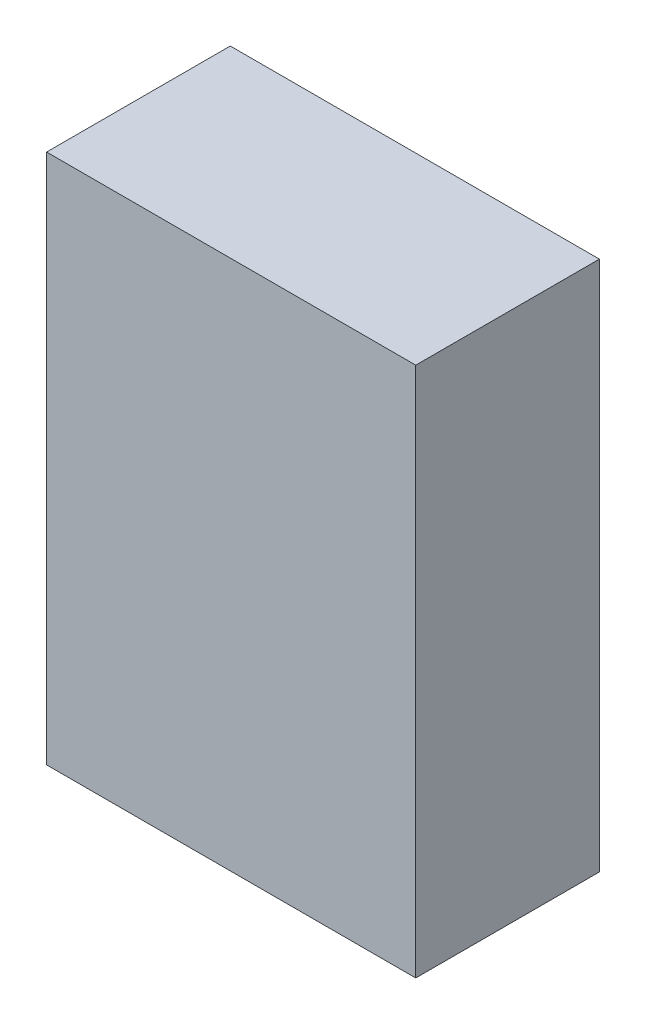
SolidWorks part; units mm, degrees
ref_plane "Front Plane" through (0, 0, 0) normal (0, 0, 1) x (1, 0, 0)
ref_plane "Top Plane" through (0, 0, 0) normal (0, 1, 0) x (1, 0, 0)
ref_plane "Right Plane" through (0, 0, 0) normal (1, 0, 0) x (0, 0, -1)
sketch "Sketch1" plane through (0, 0, 0) normal (0, 0, 1) x (1, 0, 0)
  line L0 (0, 2.89) -> (2.01, 2.89)
  line L1 (2.01, 2.89) -> (2.01, 0)
  line L2 (2.01, 0) -> (0, 0)
  line L3 (0, 0) -> (0, 2.89)
extrude "Component_Outline" add sketch "Sketch1" along normal blind 1 separate body
sketch3d "3DSketch1"
  line L0 (0, 0, 0) -> (1, 0, 0)
  line L1 (0, 0, 0) -> (0, 1, 0)
  line L2 (0, 0, 0) -> (0, 0, 1)
  point P0 (0, 0, 0)
